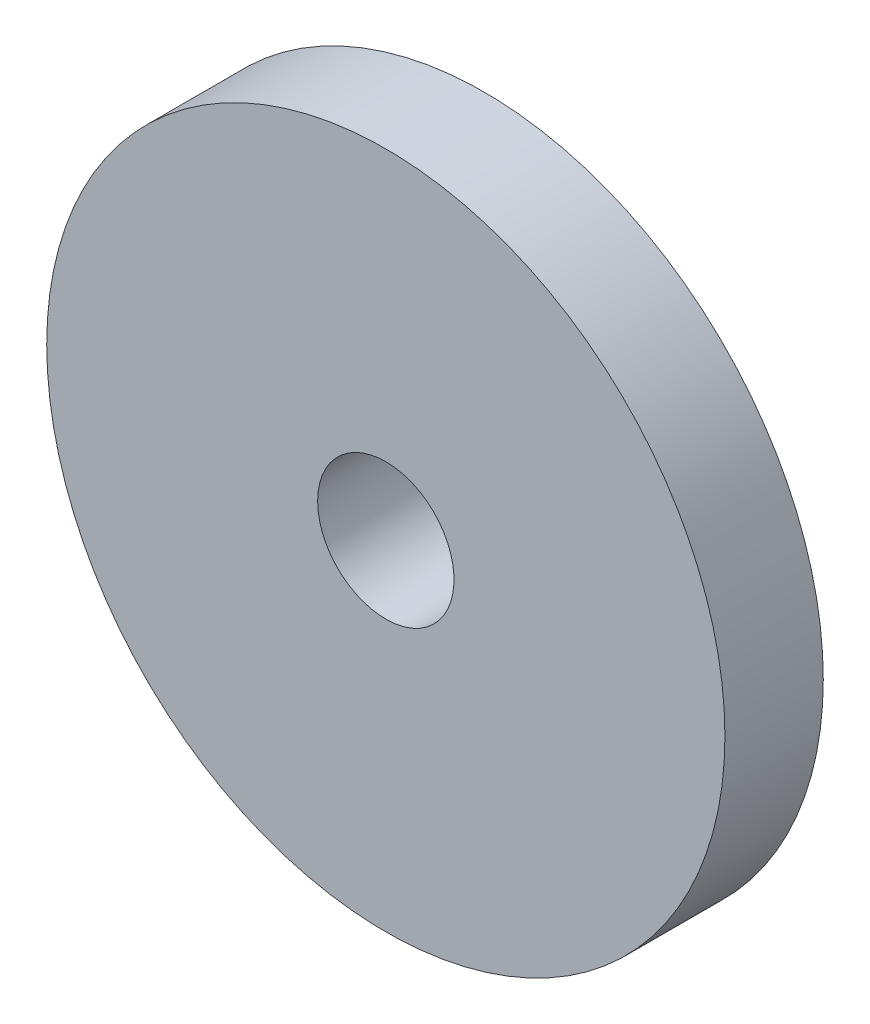
SolidWorks part; units mm, degrees
material "ABS PC"
ref_plane "Front Plane" through (0, 0, 0) normal (0, 0, 1) x (1, 0, 0)
ref_plane "Top Plane" through (0, 0, 0) normal (0, 1, 0) x (1, 0, 0)
ref_plane "Right Plane" through (0, 0, 0) normal (1, 0, 0) x (0, 0, -1)
sketch "Sketch1" plane through (0, 0, 0) normal (0, 0, 1) x (1, 0, 0)
  circle A0 centre (0, 0) radius 3.302 construction
  circle A1 centre (0, 0) radius 16.4211
  circle A2 centre (0, 0) radius 16.4211
  circle A3 centre (0, 0) radius 3.302
  dimension "D1" = 0
extrude "Boss-Extrude1" add sketch "Sketch1" along normal blind 4.7625
